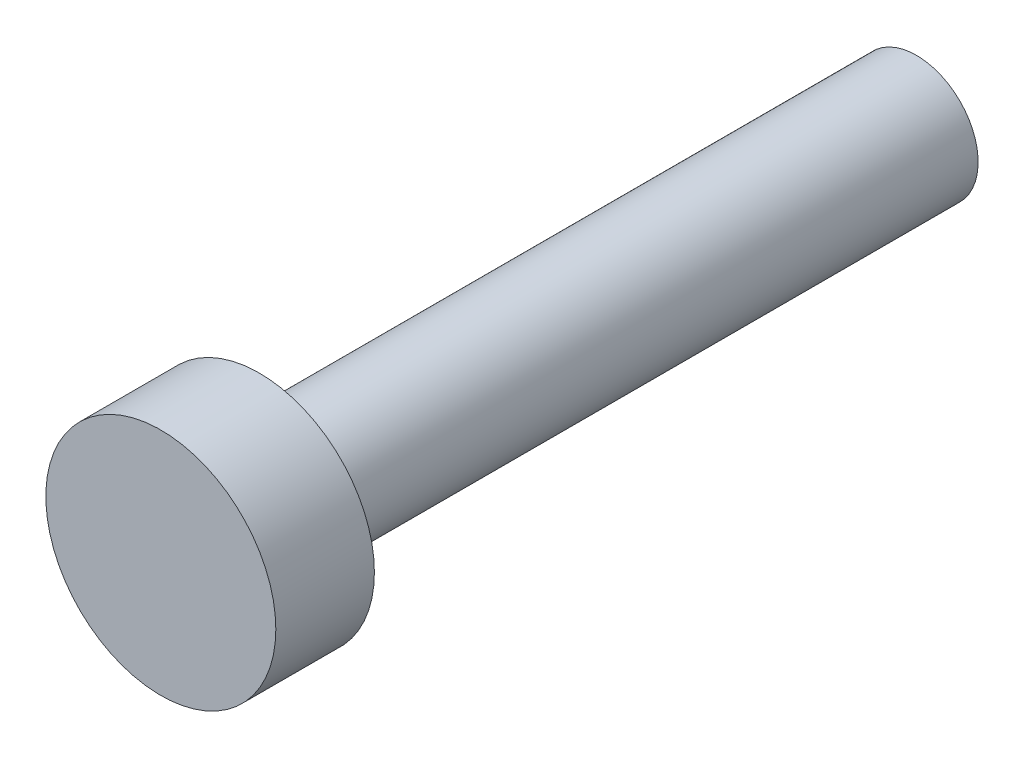
SolidWorks part; units mm, degrees
ref_plane "Plan de face" through (0, 0, 0) normal (0, 0, 1) x (1, 0, 0)
ref_plane "Plan de dessus" through (0, 0, 0) normal (0, 1, 0) x (1, 0, 0)
ref_plane "Plan de droite" through (0, 0, 0) normal (1, 0, 0) x (0, 0, -1)
sketch "Esquisse1" plane through (0, 0, 0) normal (0, 0, 1) x (1, 0, 0)
  circle A0 centre (0, 0) radius 2.8
  dimension "D1" = 5.6
extrude "Boss.-Extru.1" add sketch "Esquisse1" along normal blind 2.4
sketch "Esquisse2" plane through (0, 0, 0) normal (0, 0, -1) x (-1, 0, 0)
  circle A0 centre (0, 0) radius 1.5
  dimension "D1" = 3
extrude "Boss.-Extru.2" add sketch "Esquisse2" along normal blind 16
